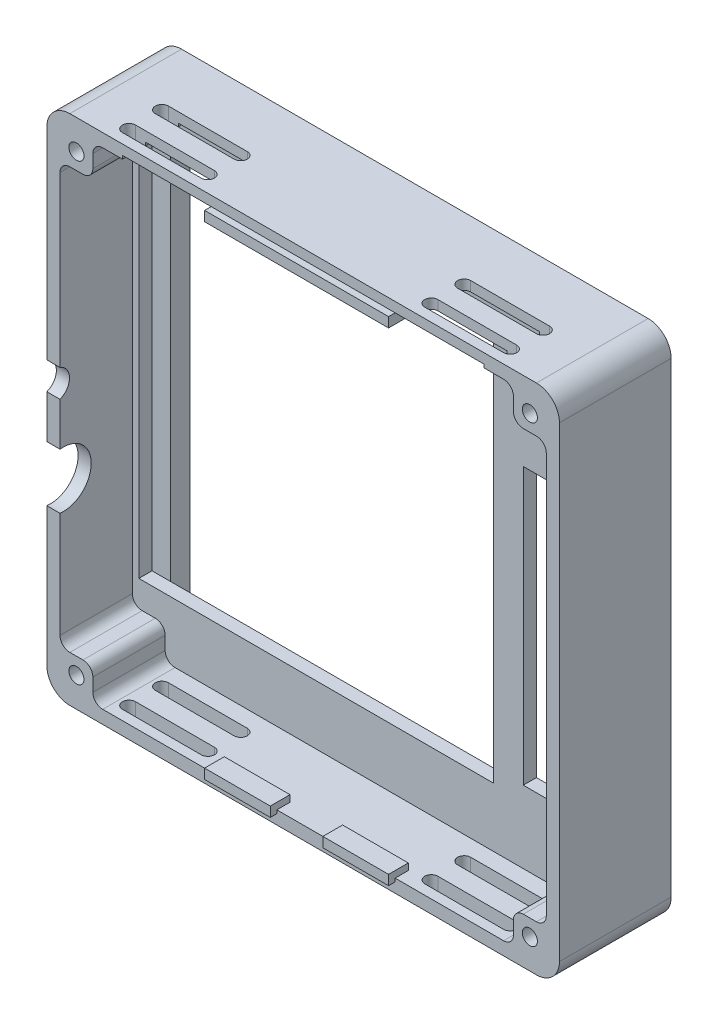
SolidWorks part; units mm, degrees
ref_plane "前视基准面" through (0, 0, 0) normal (0, 0, 1) x (1, 0, 0)
ref_plane "上视基准面" through (0, 0, 0) normal (0, 1, 0) x (1, 0, 0)
ref_plane "右视基准面" through (0, 0, 0) normal (1, 0, 0) x (0, 0, -1)
other "Configuration Table"
sketch "草图1" plane through (0, 0, 0) normal (0, 0, 1) x (1, 0, 0)
  line L1 (-39, -39) -> (39, -39)
  line L2 (-39, -39) -> (-39, 39)
  line L3 (-39, 39) -> (39, 39)
  line L4 (39, -39) -> (39, 39)
  line L5 (-39, -39) -> (39, 39) construction
  line L6 (-39, 39) -> (39, -39) construction
  point P0 (0, 0)
  dimension "D1" = 78
extrude "凸台-拉伸1" add sketch "草图1" along normal blind 6
sketch "草图2" plane through (0, 0, 6) normal (0, 0, 1) x (1, 0, 0)
  line L1 (-39, -39) -> (39, -39)
  line L2 (-39, -39) -> (-39, 39)
  line L3 (-39, 39) -> (39, 39)
  line L4 (39, -39) -> (39, 39)
  line L5 (-39, -39) -> (39, 39) construction
  line L6 (-39, 39) -> (39, -39) construction
  line L7 (37, 37) -> (-37, 37)
  line L8 (37, 37) -> (37, -37)
  line L9 (37, -37) -> (-37, -37)
  line L10 (-37, 37) -> (-37, -37)
  line L11 (37, 37) -> (-37, -37) construction
  line L12 (37, -37) -> (-37, 37) construction
  line L13 (-37, 37) -> (-32, 37)
  line L14 (-37, 37) -> (-37, 32)
  line L15 (-37, 32) -> (-32, 32)
  line L16 (-32, 37) -> (-32, 32)
  line L17 (37, 37) -> (32, 37)
  line L18 (37, 37) -> (37, 32)
  line L19 (37, 32) -> (32, 32)
  line L20 (32, 37) -> (32, 32)
  line L21 (-37, -37) -> (-32, -37)
  line L22 (-37, -37) -> (-37, -32)
  line L23 (-37, -32) -> (-32, -32)
  line L24 (-32, -37) -> (-32, -32)
  line L25 (37, -37) -> (32, -37)
  line L26 (37, -37) -> (37, -32)
  line L27 (37, -32) -> (32, -32)
  line L28 (32, -37) -> (32, -32)
  point P0 (0, 0)
  point P7 (0, 0)
  line M22 (39, -39) -> (39, 39)
  line M23 (39, 39) -> (-39, 39)
  line M24 (-39, 39) -> (-39, -39)
  line M25 (-39, -39) -> (39, -39)
  dimension "D1" = 2
  dimension "D2" = 5
extrude "凸台-拉伸2" add sketch "草图2" along normal blind 11 contours L10 L7 L8 L9 M25 M22 M23 M24 | L16 L7 L10 L15 | L7 L20 L19 L8 | L28 L9 L8 L27 | L9 L24 L23 L10
fillet "圆角1" radius 1.5 12 edges at (37, 32, 11.5) (32, 32, 11.5) (32, 37, 11.5) (37, -32, 11.5) (32, -32, 11.5) (32, -37, 11.5) (-32, -37, 11.5) (-32, -32, 11.5) (-37, -32, 11.5) (-37, 32, 11.5) (-32, 37, 11.5) (-32, 32, 11.5)
fillet "圆角2" radius 3.5 4 edges at (-39, 39, 8.5) (39, 39, 8.5) (39, -39, 8.5) (-39, -39, 8.5)
sketch "草图3" plane through (0, 0, 0) normal (0, 0, -1) x (-1, 0, 0)
  line L8 (37.5, -35.5) -> (37.5, 35.5)
  line L9 (-35.5, -37.5) -> (35.5, -37.5)
  line L10 (-37.5, 35.5) -> (-37.5, -35.5)
  line L11 (35.5, 37.5) -> (-35.5, 37.5)
  line L12 (37.5, -35.5) -> (37.5, 35.5)
  line L13 (-35.5, -37.5) -> (35.5, -37.5)
  line L14 (-37.5, 35.5) -> (-37.5, -35.5)
  line L15 (35.5, 37.5) -> (-35.5, 37.5)
  arc A8 (37.5, 35.5) -> (35.5, 37.5) centre (35.5, 35.5) ccw
  arc A9 (35.5, -37.5) -> (37.5, -35.5) centre (35.5, -35.5) ccw
  arc A10 (-37.5, -35.5) -> (-35.5, -37.5) centre (-35.5, -35.5) ccw
  arc A11 (-35.5, 37.5) -> (-37.5, 35.5) centre (-35.5, 35.5) ccw
  arc A12 (37.5, 35.5) -> (35.5, 37.5) centre (35.5, 35.5) ccw
  arc A13 (35.5, -37.5) -> (37.5, -35.5) centre (35.5, -35.5) ccw
  arc A14 (-37.5, -35.5) -> (-35.5, -37.5) centre (-35.5, -35.5) ccw
  arc A15 (-35.5, 37.5) -> (-37.5, 35.5) centre (-35.5, 35.5) ccw
  dimension "D1" = 1.5
extrude "切除-拉伸1" cut sketch "草图3" against normal blind 1
sketch "草图4" plane through (0, 0, 1) normal (0, 0, -1) x (-1, 0, 0)
  line L0 (35.5, 37.5) -> (-35.5, 37.5) construction
  line L1 (-33.2, 37.5) -> (33.2, 37.5)
  line L2 (-33.2, 37.5) -> (-33.2, -33.5)
  line L3 (-33.2, -33.5) -> (33.2, -33.5)
  line L4 (33.2, 37.5) -> (33.2, -33.5)
  line L6 (0, 0) -> (0, 26.6317) construction
  line L7 (-33.2, 37.1) -> (33.2, 37.1)
  line L8 (27.5, 37.1) -> (27.5, 37.5)
  line L9 (-27.5, 37.1) -> (-27.5, 37.5)
  line M10 (35.5, 37.5) -> (-35.5, 37.5)
  dimension "D1" = 71
  dimension "D2" = 66.4
  dimension "D3" = 0.4
  dimension "D4" = 55
extrude "切除-拉伸2" cut sketch "草图4" against normal blind 3 contours L3 L6 L7 L2 | L6 L3 L4 L7 | L7 L6 L9 M10 | L6 L7 L8 L1
sketch "草图5" plane through (0, 0, 1) normal (0, 0, -1) x (-1, 0, 0)
  line L0 (-35.5, 39) -> (35.5, 39) construction
  line L1 (-34.5, -34.5) -> (34.5, -34.5) construction
  line L2 (-34.5, -34.5) -> (-34.5, 34.5) construction
  line L3 (-34.5, 34.5) -> (34.5, 34.5) construction
  line L4 (34.5, -34.5) -> (34.5, 34.5) construction
  line L5 (-34.5, -34.5) -> (34.5, 34.5) construction
  line L6 (-34.5, 34.5) -> (34.5, -34.5) construction
  circle A0 centre (-34.5, 34.5) radius 1.15
  circle A1 centre (34.5, 34.5) radius 1.15
  circle A2 centre (34.5, -34.5) radius 1.15
  circle A3 centre (-34.5, -34.5) radius 1.15
  point P0 (0, 0)
  dimension "D2" = 2.3
  dimension "D1" = 4.5
extrude "切除-拉伸3" cut sketch "草图5" against normal through all
sketch "草图6" plane through (0, 0, 4) normal (0, 0, -1) x (-1, 0, 0)
  line L1 (-27.5, 37.5) -> (27.5, 37.5)
  line L2 (-27.5, 37.5) -> (-27.5, 35.5)
  line L3 (-27.5, 35.5) -> (27.5, 35.5)
  line L4 (27.5, 37.5) -> (27.5, 35.5)
  line L5 (-18, 30) -> (36, 30)
  line L6 (-18, 30) -> (-18, -28)
  line L7 (-18, -28) -> (36, -28)
  line L8 (36, 30) -> (36, -28)
  line L9 (-35, 16) -> (-22.5, 16)
  line L10 (-35, 16) -> (-35, -26)
  line L11 (-35, -26) -> (-22.5, -26)
  line L12 (-22.5, 16) -> (-22.5, -26)
  dimension "D1" = 2
  dimension "D2" = 54
  dimension "D3" = 30
  dimension "D4" = 58
  dimension "D5" = 36
  dimension "D6" = 22.5
  dimension "D7" = 12.5
  dimension "D8" = 42
  dimension "D9" = 16
extrude "切除-拉伸4" cut sketch "草图6" against normal through all
sketch "草图7" plane through (0, 0, 17) normal (0, 0, 1) x (1, 0, 0)
  line L0 (-15.0283, 0) -> (15.498, 0) construction
  line L17 (0, -8.9343) -> (0, 15.7561) construction
  line L20 (35.5, -37.5) -> (-35.5, -37.5) construction
  line L21 (14, -37.5) -> (4, -37.5)
  line L22 (14, -37.5) -> (14, -36)
  line L23 (14, -36) -> (4, -36)
  line L24 (4, -37.5) -> (4, -36)
  line L25 (-27.5, 37.5) -> (27.5, 37.5) construction
  line L26 (-4, -37.5) -> (-14, -37.5)
  line L27 (-4, -37.5) -> (-4, -36)
  line L28 (-4, -36) -> (-14, -36)
  line L29 (-14, -37.5) -> (-14, -36)
  line L30 (-14, 37.5) -> (14, 37.5)
  line L31 (-14, 37.5) -> (-14, 36)
  line L32 (-14, 36) -> (14, 36)
  line L33 (14, 37.5) -> (14, 36)
  dimension "D1" = 1.5
  dimension "D2" = 28
  dimension "D4" = 1.5
  dimension "D5" = 28
  dimension "D6" = 8
extrude "凸台-拉伸3" add sketch "草图7" along normal blind 1 and the other way blind 2
sketch "草图8" plane through (-39, 0, 0) normal (1, 0, 0) x (0, 0, -1)
  line L0 (-17, -35.5) -> (0, -35.5) construction
  line L1 (-17, -35.5) -> (-17, 35.5) construction
  line L2 (-17, 4.8) -> (-17, 0.6) construction
  circle A0 centre (-16.5, -10.2) radius 4.25
  circle A1 centre (-17.8, 2.7) radius 2.2472
  dimension "D1" = 8.5
  dimension "D4" = 4.2
  dimension "D2" = 25.3
  dimension "D3" = 0.5
  dimension "D5" = 38.2
  dimension "D6" = 0.8
extrude "切除-拉伸5" cut sketch "草图8" along normal blind 10
sketch "草图9" plane through (0, -39, 0) normal (0, -1, 0) x (1, 0, 0)
  line L0 (-29, 14.5) -> (-17, 14.5) construction
  line L1 (-29, 15.5) -> (-17, 15.5)
  line L2 (-29, 13.5) -> (-17, 13.5)
  line L3 (-39, 0) -> (-39, 17) construction
  line L4 (-35.5, 17) -> (35.5, 17) construction
  line L5 (-29, 9.5) -> (-17, 9.5) construction
  line L6 (-29, 10.5) -> (-17, 10.5)
  line L7 (-29, 8.5) -> (-17, 8.5)
  line L8 (-29, 14.5) -> (-29, 9.5) construction
  line L9 (0, -1000) -> (0, 49000) construction
  line L11 (29, 9.5) -> (17, 9.5) construction
  line L12 (29, 10.5) -> (17, 10.5)
  line L13 (29, 8.5) -> (17, 8.5)
  line L14 (29, 14.5) -> (17, 14.5) construction
  line L15 (29, 15.5) -> (17, 15.5)
  line L16 (29, 13.5) -> (17, 13.5)
  arc A0 (-29, 15.5) -> (-29, 13.5) centre (-29, 14.5) ccw
  arc A1 (-17, 13.5) -> (-17, 15.5) centre (-17, 14.5) ccw
  arc A2 (-29, 10.5) -> (-29, 8.5) centre (-29, 9.5) ccw
  arc A3 (-17, 8.5) -> (-17, 10.5) centre (-17, 9.5) ccw
  arc A4 (29, 10.5) -> (29, 8.5) centre (29, 9.5) cw
  arc A5 (17, 8.5) -> (17, 10.5) centre (17, 9.5) cw
  arc A6 (29, 15.5) -> (29, 13.5) centre (29, 14.5) cw
  arc A7 (17, 13.5) -> (17, 15.5) centre (17, 14.5) cw
  point P2 (-23, 14.5)
  point P15 (-23, 9.5)
  point P27 (23, 9.5)
  point P34 (23, 14.5)
  dimension "D3" = 1
  dimension "D1" = 12
  dimension "D2" = 10
  dimension "D4" = 2.5
  dimension "D6" = 5
  dimension "D5" = 2
extrude "切除-拉伸6" cut sketch "草图9" against normal through all
sketch "草图10" plane through (0, 0, 1) normal (0, 0, -1) x (-1, 0, 0)
  line L0 (-33.2, 37.1) -> (-33.2, 16) construction
  line L1 (-34.5, 35.65) -> (-33.2, 35.65)
  line L2 (-34.5, 35.65) -> (-34.5, 33.35)
  line L3 (-34.5, 33.35) -> (-33.2, 33.35)
  line L4 (-33.2, 35.65) -> (-33.2, 33.35)
  line L5 (33.2, 37.1) -> (33.2, 30) construction
  line L6 (34.5, 35.65) -> (33.2, 35.65)
  line L7 (34.5, 35.65) -> (34.5, 33.35)
  line L8 (34.5, 33.35) -> (33.2, 33.35)
  line L9 (33.2, 35.65) -> (33.2, 33.35)
  circle A0 centre (-34.5, 34.5) radius 1.15 construction
  circle A1 centre (34.5, 34.5) radius 1.15 construction
extrude "切除-拉伸7" cut sketch "草图10" against normal blind 3
